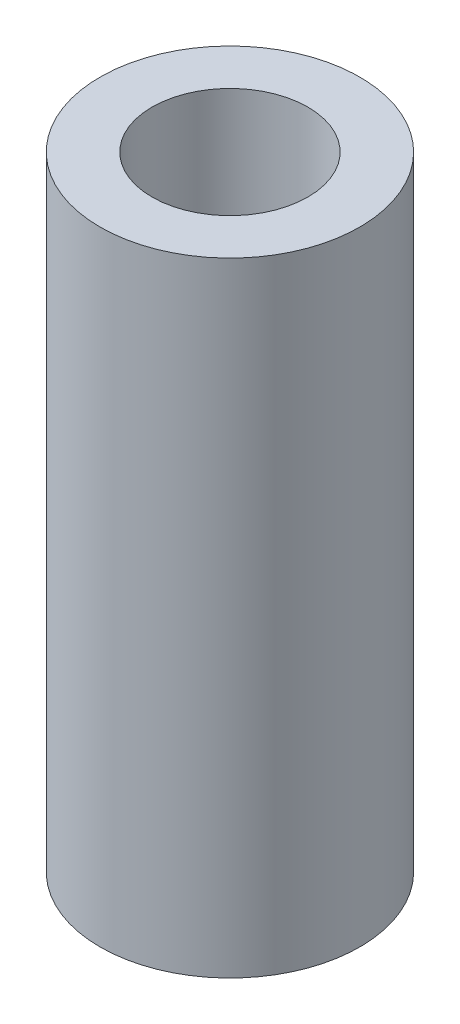
SolidWorks part; units mm, degrees
ref_plane "前视基准面" through (0, 0, 0) normal (0, 0, 1) x (1, 0, 0)
ref_plane "上视基准面" through (0, 0, 0) normal (0, 1, 0) x (1, 0, 0)
ref_plane "右视基准面" through (0, 0, 0) normal (1, 0, 0) x (0, 0, -1)
sketch "Sketch1" plane through (0, 0, 0) normal (0, 1, 0) x (1, 0, 0)
  circle A0 centre (0, 0) radius 1.5
  circle A1 centre (0, 0) radius 2.5
extrude "Boss-Extrude1" add sketch "Sketch1" along normal blind 12
